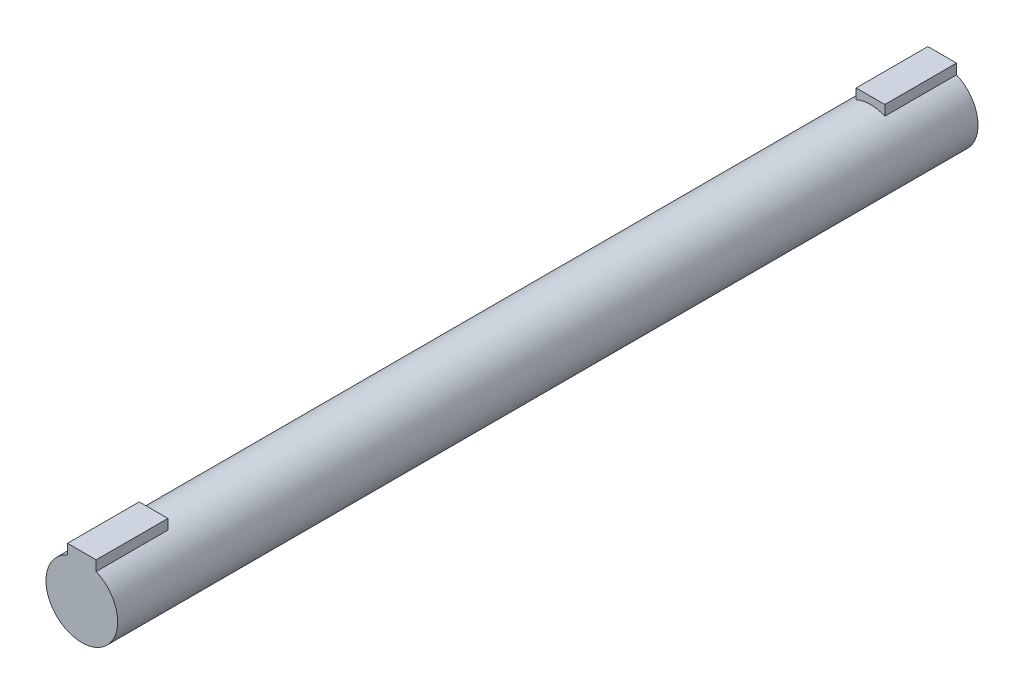
SolidWorks part; units mm, degrees
ref_plane "前视基准面" through (0, 0, 0) normal (0, 0, 1) x (1, 0, 0)
ref_plane "上视基准面" through (0, 0, 0) normal (0, 1, 0) x (1, 0, 0)
ref_plane "右视基准面" through (0, 0, 0) normal (1, 0, 0) x (0, 0, -1)
sketch "草图1" plane through (0, 0, 0) normal (0, 0, 1) x (1, 0, 0)
  line L0 (0, 5.9389) -> (0, -6.079) construction
  line L2 (-1, 3) -> (1, 3)
  line L3 (-1, 3) -> (-1, 2.2913)
  line L5 (1, 3) -> (1, 2.2913)
  arc A0 (-1, 2.2913) -> (1, 2.2913) centre (0, 0) ccw
  dimension "D1" = 5
  dimension "D2" = 2
  dimension "D3" = 1
  dimension "D4" = 3
extrude "凸台-拉伸1" add sketch "草图1" along normal blind 5
sketch "草图2" plane through (0, 0, 5) normal (0, 0, 1) x (1, 0, 0)
  circle A0 centre (0, 0) radius 2.5
extrude "凸台-拉伸2" add sketch "草图2" along normal blind 50
sketch "草图3" plane through (0, 0, 55) normal (0, 0, 1) x (1, 0, 0)
  line L0 (0, 3.8872) -> (0, -3.4389) construction
  line L2 (-1, 3) -> (1, 3)
  line L3 (-1, 3) -> (-1, 2.2913)
  line L5 (1, 3) -> (1, 2.2913)
  arc A0 (-1, 2.2913) -> (1, 2.2913) centre (0, 0) ccw
extrude "凸台-拉伸3" add sketch "草图3" along normal blind 5
